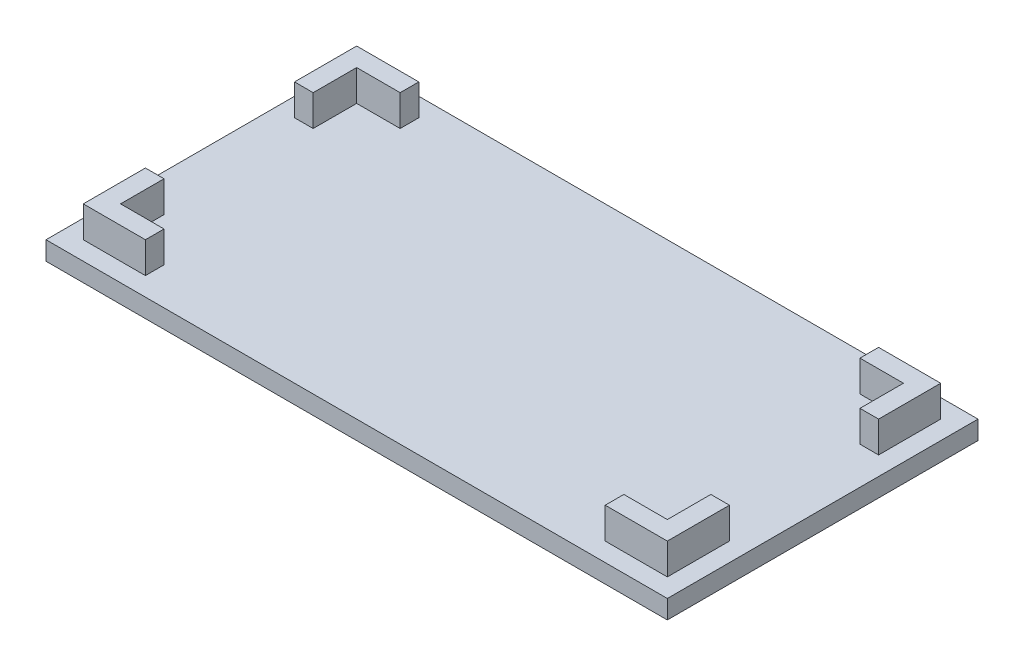
SolidWorks part; units mm, degrees
ref_plane "Front Plane" through (0, 0, 0) normal (0, 0, 1) x (1, 0, 0)
ref_plane "Top Plane" through (0, 0, 0) normal (0, 1, 0) x (1, 0, 0)
ref_plane "Right Plane" through (0, 0, 0) normal (1, 0, 0) x (0, 0, -1)
sketch "Sketch2" plane through (0, 0, 0) normal (0, 1, 0) x (1, 0, 0)
  line L1 (0, 0) -> (100, 0)
  line L2 (0, 0) -> (0, 50)
  line L3 (0, 50) -> (100, 50)
  line L4 (100, 0) -> (100, 50)
  dimension "D1" = 100
  dimension "D2" = 50
extrude "Boss-Extrude1" add sketch "Sketch2" along normal blind 3
sketch "Sketch3" plane through (0, 3, 0) normal (0, 1, 0) x (1, 0, 0)
  line L0 (3, 37) -> (3, 47)
  line L1 (3, 47) -> (13, 47)
  line L2 (13, 47) -> (13, 44)
  line L3 (13, 44) -> (6, 44)
  line L4 (6, 44) -> (6, 37)
  line L5 (6, 37) -> (3, 37)
  line L24 (100, 50) -> (0, 50) construction
  line L25 (0, 50) -> (0, 0) construction
  line L26 (13, 3) -> (3, 3)
  line L27 (3, 3) -> (3, 13)
  line L28 (3, 13) -> (6, 13)
  line L29 (6, 13) -> (6, 6)
  line L30 (6, 6) -> (13, 6)
  line L31 (13, 6) -> (13, 3)
  line L32 (97, 13) -> (97, 3)
  line L33 (97, 3) -> (87, 3)
  line L34 (87, 3) -> (87, 6)
  line L35 (87, 6) -> (94, 6)
  line L36 (94, 6) -> (94, 13)
  line L37 (94, 13) -> (97, 13)
  line L38 (87, 47) -> (97, 47)
  line L39 (97, 47) -> (97, 37)
  line L40 (97, 37) -> (94, 37)
  line L41 (94, 37) -> (94, 44)
  line L42 (94, 44) -> (87, 44)
  line L43 (87, 44) -> (87, 47)
  line L44 (0, 0) -> (100, 0) construction
  line L45 (100, 0) -> (100, 50) construction
  dimension "D1" = 3
  dimension "D2" = 3
  dimension "D3" = 3
  dimension "D4" = 10
  dimension "D5" = 10
  dimension "D6" = 3
  dimension "D7" = 3
extrude "Boss-Extrude2" add sketch "Sketch3" along normal blind 5
